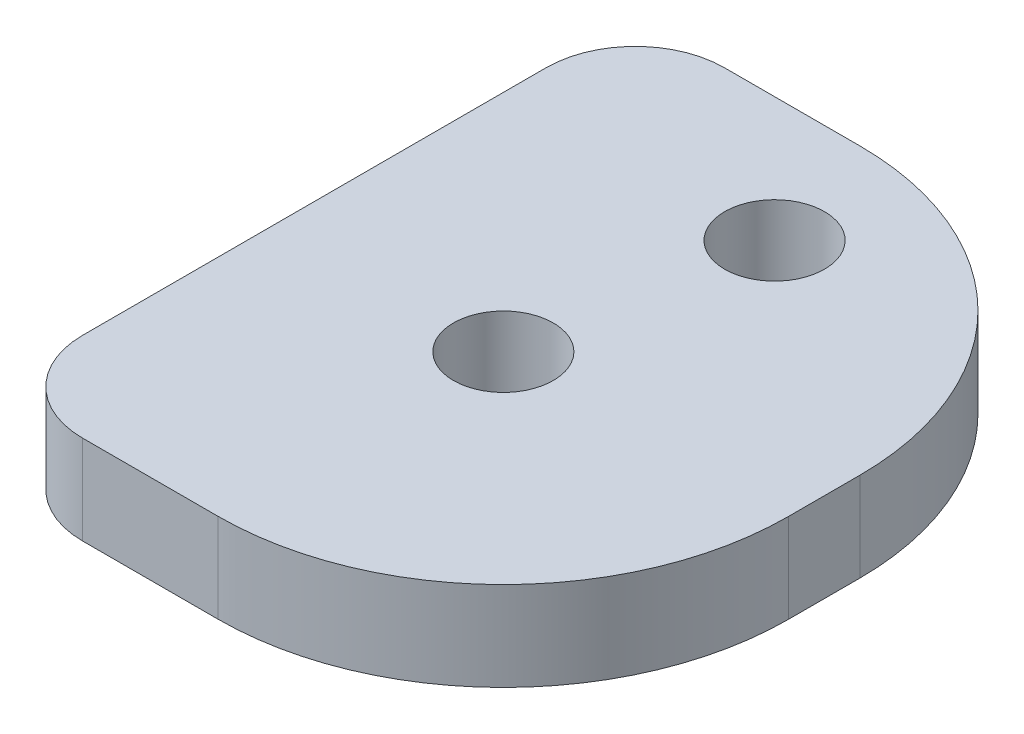
SolidWorks part; units mm, degrees
ref_plane "Front Plane" through (0, 0, 0) normal (0, 0, 1) x (1, 0, 0)
ref_plane "Top Plane" through (0, 0, 0) normal (0, 1, 0) x (1, 0, 0)
ref_plane "Right Plane" through (0, 0, 0) normal (1, 0, 0) x (0, 0, -1)
sketch "Sketch1" plane through (0, 0, 0) normal (0, 1, 0) x (1, 0, 0)
  line L1 (-25.4, 11.43) -> (25.4, 11.43)
  line L2 (-25.4, 11.43) -> (-25.4, -11.43)
  line L3 (-25.4, -11.43) -> (25.4, -11.43)
  line L4 (25.4, 11.43) -> (25.4, -11.43)
  dimension "D1" = 22.86
  dimension "D2" = 50.8
  dimension "D3" = 11.43
  dimension "D4" = 25.4
extrude "Boss-Extrude1" add sketch "Sketch1" along normal blind 3.175
fillet "Fillet1" radius 10.16 2 edges at (-25.4, 1.5875, 11.43) (25.4, 1.5875, 11.43)
sketch "Sketch3" plane through (0, 3.175, 0) normal (0, 1, 0) x (1, 0, 0)
  line L0 (-7.7526, -1.27) -> (18.5521, -1.27) construction
  circle A0 centre (15.24, -1.27) radius 1.778
  circle A1 centre (16.637, 6.9948) radius 1.778
  arc A2 (15.24, -11.43) -> (25.4, -1.27) centre (15.24, -1.27) ccw construction
  circle A3 centre (-3.81, -1.27) radius 1.778
  dimension "D1" = 3.556
  dimension "D2" = 3.556
  dimension "D6" = 3.556
  dimension "D3" = 8.382
  dimension "D4" = 1.397
  dimension "D5" = 19.05
extrude "Cut-Extrude1" cut sketch "Sketch3" against normal through all
fillet "Fillet3" radius 10.16 2 edges at (-25.4, 1.5875, -11.43) (25.4, 1.5875, -11.43)
sketch "Sketch4" plane through (0, 3.175, 0) normal (0, 1, 0) x (1, 0, 0)
  line L0 (7.239, 11.43) -> (7.239, -11.43)
  line L1 (-25.4, 1.27) -> (-25.4, -1.27) construction
  line L2 (7.239, 11.43) -> (-25.4, 11.43)
  line L5 (15.24, 11.43) -> (-15.24, 11.43) construction
  line L7 (-15.24, -11.43) -> (15.24, -11.43) construction
  line L9 (7.239, -11.43) -> (-25.4, -11.43)
  line L10 (-25.4, 11.43) -> (-25.4, -11.43)
  dimension "D1" = 18.161
extrude "Cut-Extrude2" cut sketch "Sketch4" against normal through all
fillet "Fillet9" radius 3.175 2 edges at (7.239, 1.5875, 11.43) (7.239, 1.5875, -11.43)
equation "\"D4@Sketch1\"=\"D2@Sketch1\"/2"
equation "\"D3@Sketch1\"=\"D1@Sketch1\"/2"
